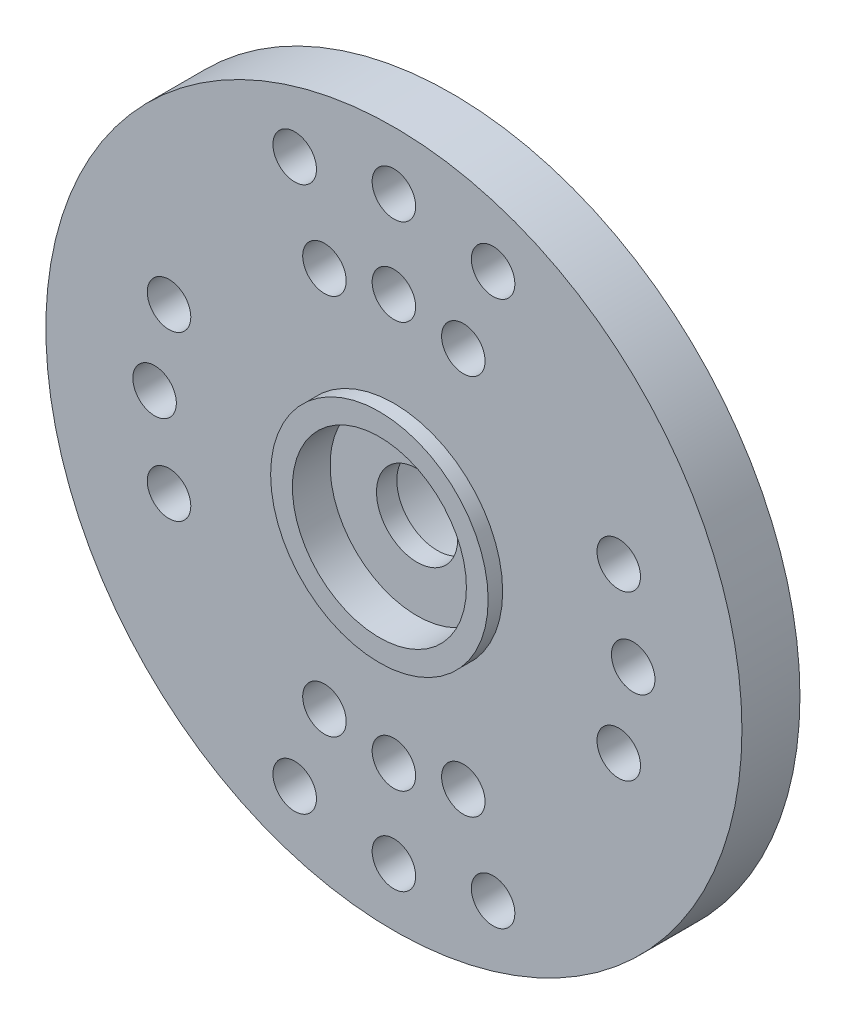
SolidWorks part; units mm, degrees
material "Полибутадиен (PB)"
ref_plane "Спереди" through (0, 0, 0) normal (0, 0, 1) x (1, 0, 0)
ref_plane "Сверху" through (0, 0, 0) normal (0, 1, 0) x (1, 0, 0)
ref_plane "Справа" through (0, 0, 0) normal (1, 0, 0) x (0, 0, -1)
sketch "Эскиз1" plane through (0, 0, 0) normal (1, 0, 0) x (0, 0, -1)
  line L0 (0, 3.75) -> (0, 12)
  line L1 (0, 12) -> (2, 12)
  line L2 (2, 12) -> (2, 4.5)
  line L3 (2, 4.5) -> (4.5, 4.5)
  line L4 (4.5, 4.5) -> (4.5, 3)
  line L5 (4.5, 3) -> (1.5, 3)
  line L6 (-0.5, 3.75) -> (0, 3.75)
  line L7 (-0.5, 3.75) -> (-0.5, 3)
  line L8 (-0.5, 3) -> (0.8, 3)
  line L9 (0.8, 3) -> (0.8, 1.4)
  line L10 (0.8, 1.4) -> (1.5, 1.4)
  line L11 (1.5, 3) -> (1.5, 1.4)
  dimension "D1" = 2
  dimension "D2" = 3
  dimension "D3" = 12
  dimension "D4" = 4.5
  dimension "D5" = 3
  dimension "D6" = 3.75
  dimension "D7" = 3
  dimension "D8" = 0.5
  dimension "D9" = 4.5
  dimension "D10" = 1.3
  dimension "D11" = 1.4
ref_axis "Ось1" through (0, 0, 50) along (0, 0, -1)
revolve "Повернуть1" add sketch "Эскиз1" angle 360 about axis through (0, 0, 50) along (0, 0, -1)
sketch "Эскиз2" plane through (0, 0, 0) normal (0, 0, 1) x (1, 0, 0)
  line L0 (0, 0) -> (8.25, 0) construction
  line L1 (0, 0) -> (7.7525, -2.8217) construction
  line L2 (0, 0) -> (0, 7) construction
  line L3 (0, 0) -> (2.3941, 6.5778) construction
  line L4 (0, 0) -> (0, 7) construction
  line L5 (0, 0) -> (-2.3941, 6.5778) construction
  circle A0 centre (8.25, 0) radius 0.75
  circle A1 centre (7.7525, -2.8217) radius 0.75
  circle A2 centre (7.7525, 2.8217) radius 0.75
  circle A3 centre (-8.25, 0) radius 0.75
  circle A4 centre (-7.7525, -2.8217) radius 0.75
  circle A5 centre (-7.7525, 2.8217) radius 0.75
  circle A6 centre (0, 7) radius 0.75
  circle A8 centre (0, 10) radius 0.75
  circle A9 centre (2.3941, 6.5778) radius 0.75
  circle A10 centre (3.4202, 9.3969) radius 0.75
  circle A11 centre (-2.3941, 6.5778) radius 0.75
  circle A12 centre (-3.4202, 9.3969) radius 0.75
  circle A13 centre (0, -7) radius 0.75
  circle A14 centre (0, -10) radius 0.75
  circle A15 centre (3.4202, -9.3969) radius 0.75
  circle A16 centre (2.3941, -6.5778) radius 0.75
  circle A17 centre (-2.3941, -6.5778) radius 0.75
  circle A18 centre (-3.4202, -9.3969) radius 0.75
  point P12 (0, 0)
  point P20 (0, 0)
  point P51 (0, 0)
  dimension "D1" = 1.5
  dimension "D7" = 1.5
  dimension "D9" = 1.5
  dimension "D2" = 8.25
  dimension "D4" = 20
  dimension "D8" = 7
  dimension "D10" = 10
  dimension "D12" = 20
  dimension "D14" = 20
  dimension "D3" = 2
  dimension "D5" = 2
  dimension "D6" = 2
  dimension "D11" = 2
  dimension "D13" = 2
  dimension "D15" = 2
extrude "Вырез-Вытянуть1" cut sketch "Эскиз2" against normal through all
